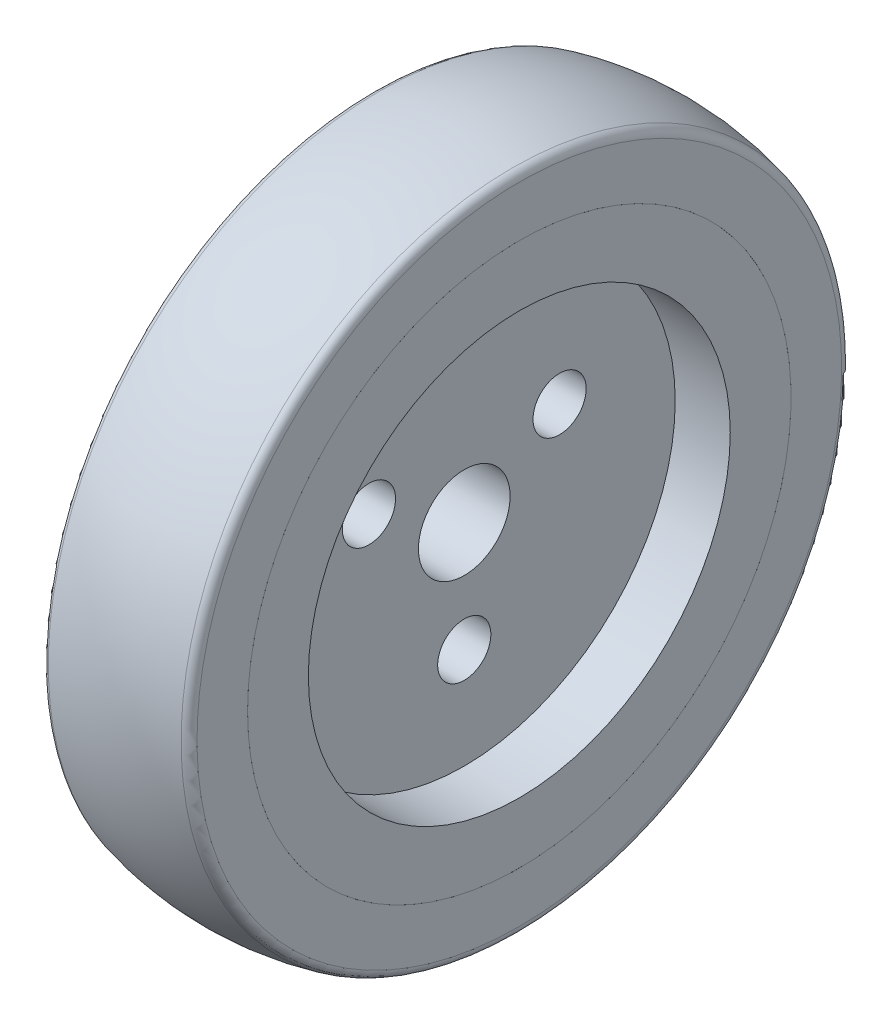
SolidWorks part; units mm, degrees
material "Alliage 1060"
ref_plane "Plan de face" through (0, 0, 0) normal (0, 0, 1) x (1, 0, 0)
ref_plane "Plan de dessus" through (0, 0, 0) normal (0, 1, 0) x (1, 0, 0)
ref_plane "Plan de droite" through (0, 0, 0) normal (1, 0, 0) x (0, 0, -1)
sketch "Esquisse2" plane through (0, 0, 0) normal (0, 0, 1) x (1, 0, 0)
  line L0 (4, 2.5) -> (-4, 2.5)
  line L1 (-4, 2.5) -> (-4, 17.9568)
  line L2 (-2.4413, 18.3) -> (2.4413, 18.3) construction
  line L9 (4, 17.9568) -> (4, 2.5)
  line L10 (0, 18.5) -> (0, 0) construction
  line L11 (-12.5, 0) -> (12.5, 0) construction
  arc A0 (-4, 17.9568) -> (4, 17.9568) centre (0, 3.5) cw
  dimension "D1" = 37
  dimension "D2" = 15
  dimension "D3" = 0.2
  dimension "D4" = 4.8826
  dimension "D5" = 8
  dimension "D6" = 5
revolve "Révolution1" add sketch "Esquisse2" angle 360 about L11
sketch "Esquisse3" plane through (0, 0, 0) normal (0, 0, 1) x (1, 0, 0)
  line L0 (-4, 17.9568) -> (-4, -17.9568) construction
  line L1 (4, -17.9568) -> (4, 17.9568) construction
  line L2 (-4, 14.8137) -> (-4, 14.8126)
  line L3 (4, 14.8126) -> (4, 14.8137)
  line L4 (-4, 0) -> (4, 0) construction
  arc A0 (4, 17.9568) -> (-4, 17.9568) centre (0, 3.5) ccw construction
  arc A1 (4, 14.8126) -> (-4, 14.8126) centre (0, 3.5) ccw
  arc A2 (3.2, 15.0655) -> (-3.2, 15.0655) centre (0, 3.5) ccw
  arc A3 (4, 14.8137) -> (-4, 14.8137) centre (0, 3.5) ccw
  arc A4 (3.9997, 14.8128) -> (-3.9997, 14.8128) centre (0, 3.5) ccw construction
  dimension "D1" = 3
  dimension "D2" = 0.001
revolve "Enlèvement de matière-Révolution1" cut sketch "Esquisse3" angle 360 about L4
fillet "Congé1" radius 0.5 2 edges at (-4, -17.9568, 0) (4, -17.9568, 0)
sketch "Esquisse4" plane through (0, 0, 0) normal (0, 0, 1) x (1, 0, 0)
  line L0 (-4, 2.5) -> (-4.5, 2.5)
  line L1 (-4.5, 2.5) -> (-4.5, 11.5)
  line L3 (-4, 17.5712) -> (-4, -17.5712) construction
  line L4 (-4, 11.5) -> (-4, 2.5)
  line L5 (4, 0) -> (-4, 0) construction
  line L6 (4, -17.5712) -> (4, 17.5712) construction
  line L7 (-4.5, 11.5) -> (-4, 11.5)
  dimension "D1" = 23
  dimension "D3" = 0.5
revolve "Révolution2" add sketch "Esquisse4" angle 360 about L5
sketch "Esquisse6" plane through (0, 0, 0) normal (0, 0, 1) x (1, 0, 0)
  line L0 (4, 11.5) -> (1, 11.5)
  line L1 (4, -17.5712) -> (4, 17.5712) construction
  line L2 (1, 11.5) -> (1, 0)
  line L3 (1, 0) -> (4, 0) construction
  line L4 (4, 0) -> (4, 11.5)
  line L5 (1, 0) -> (4, 0)
  dimension "D1" = 23
  dimension "D2" = 3
revolve "Enlèvement de matière-Révolution2" cut sketch "Esquisse6" angle 360 about L3
hole_wizard "Diamètre du perçage Ø3.5 (3.5)1" positions "Esquisse9" profile "Esquisse8" hole size "Ø3.5" standard "Iso" end condition through all
sketch "Esquisse9" plane through (1, 0, 0) normal (1, 0, 0) x (0, 0, -1)
  circle A0 centre (0, 0) radius 6
  point P5 (0, -6)
  dimension "D1" = 12
sketch "Esquisse8" plane through (1, -6, 0) normal (0, 1, 0) x (0, 0, -1)
  line L0 (0, 0) -> (0, 5.5)
  line L1 (0, 5.5) -> (1.45, 5.5)
  line L2 (1.45, 5.5) -> (1.45, 0)
  line L5 (1.45, 0) -> (0, 0)
  line L11 (0, -6.35) -> (0, 107.95) construction
  dimension "Diamètre du perçage jusqu'au prochain" = 2.9
  dimension "Profondeur du perçage jusqu'au prochain" = 5.5
pattern_circular "Répétition circulaire1" count 3 over 360 about axis through (0, 0, 0) along (1, 0, 0) of "Diamètre du perçage Ø3.5 (3.5)1"
